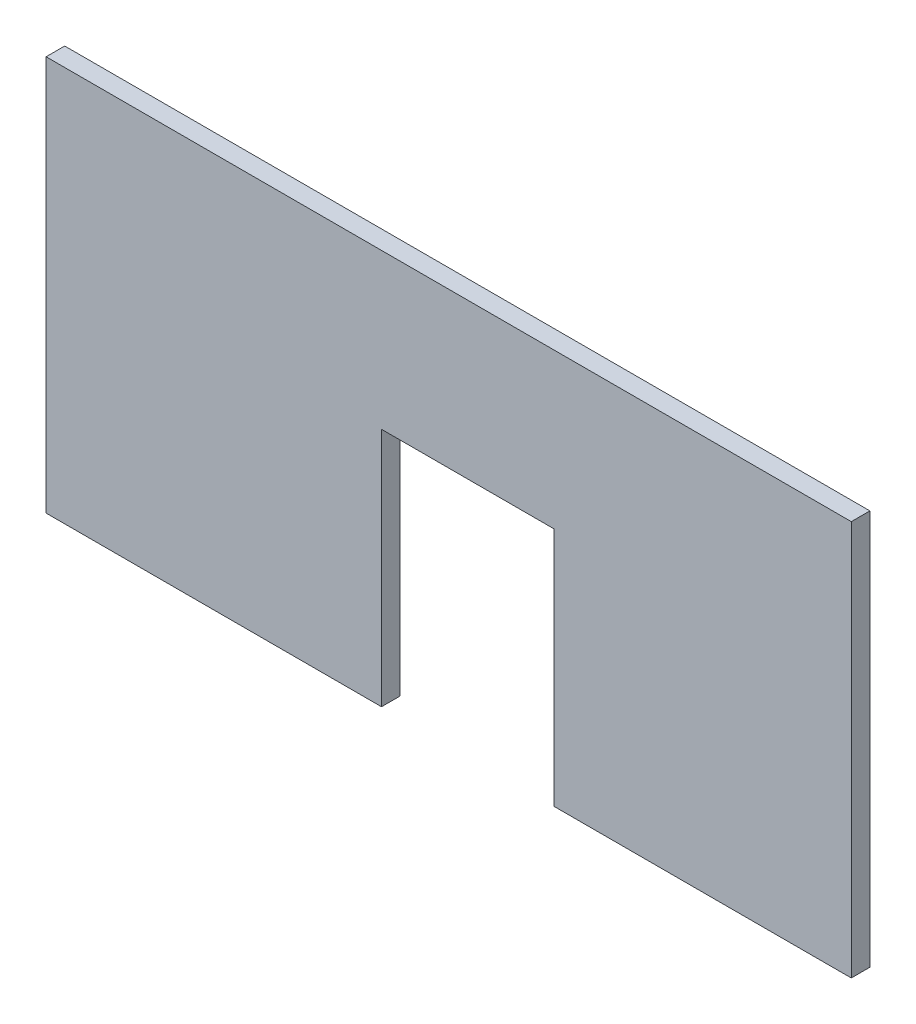
SolidWorks part; units mm, degrees
ref_plane "Front Plane" through (0, 0, 0) normal (0, 0, 1) x (1, 0, 0)
ref_plane "Top Plane" through (0, 0, 0) normal (0, 1, 0) x (1, 0, 0)
ref_plane "Right Plane" through (0, 0, 0) normal (1, 0, 0) x (0, 0, -1)
sketch "Sketch1" plane through (0, 0, 0) normal (0, 0, 1) x (1, 0, 0)
  line L0 (-35.7512, 1576.4855) -> (-35.7512, 1705.5429)
  line L1 (216.5353, 1576.4855) -> (56.9829, 1576.4855)
  line L2 (216.5353, 1576.4855) -> (216.5353, 1788.7384)
  line L3 (216.5353, 1788.7384) -> (-215.8753, 1788.7384)
  line L4 (-215.8753, 1576.4855) -> (-215.8753, 1788.7384)
  line L5 (-35.7512, 1705.5429) -> (56.9829, 1705.5429)
  line L6 (56.9829, 1705.5429) -> (56.9829, 1576.4855)
  line L7 (-0.1944, 1575.6001) -> (-0.1944, 1720.2473) construction
  line L8 (-35.7512, 1576.4855) -> (-215.8753, 1576.4855)
extrude "Boss-Extrude1" add sketch "Sketch1" along normal blind 10 from offset 48
